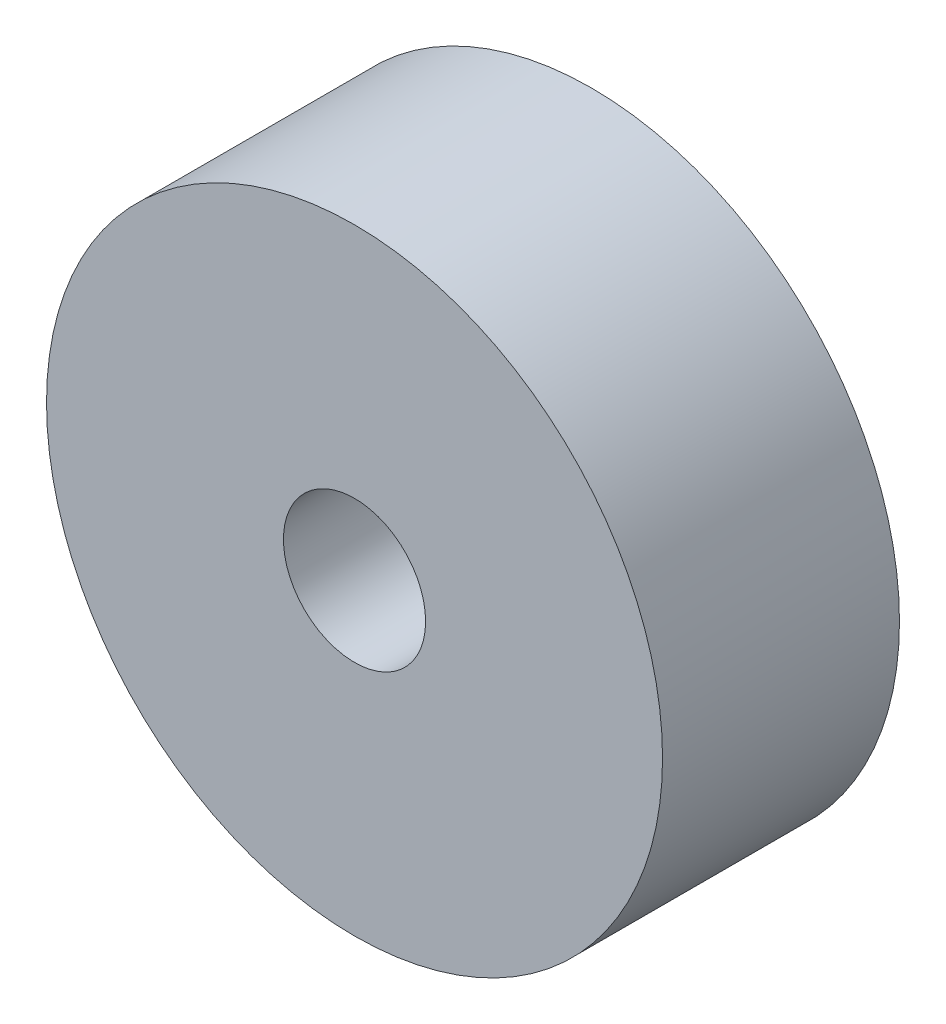
SolidWorks part; units mm, degrees
ref_plane "前视基准面" through (0, 0, 0) normal (0, 0, 1) x (1, 0, 0)
ref_plane "上视基准面" through (0, 0, 0) normal (0, 1, 0) x (1, 0, 0)
ref_plane "右视基准面" through (0, 0, 0) normal (1, 0, 0) x (0, 0, -1)
sketch "草图1" plane through (0, 0, 0) normal (0, 0, 1) x (1, 0, 0)
  circle A0 centre (0, 0) radius 1.5
  circle A1 centre (0, 0) radius 6.5
extrude "凸台-拉伸1" add sketch "草图1" along normal blind 5
